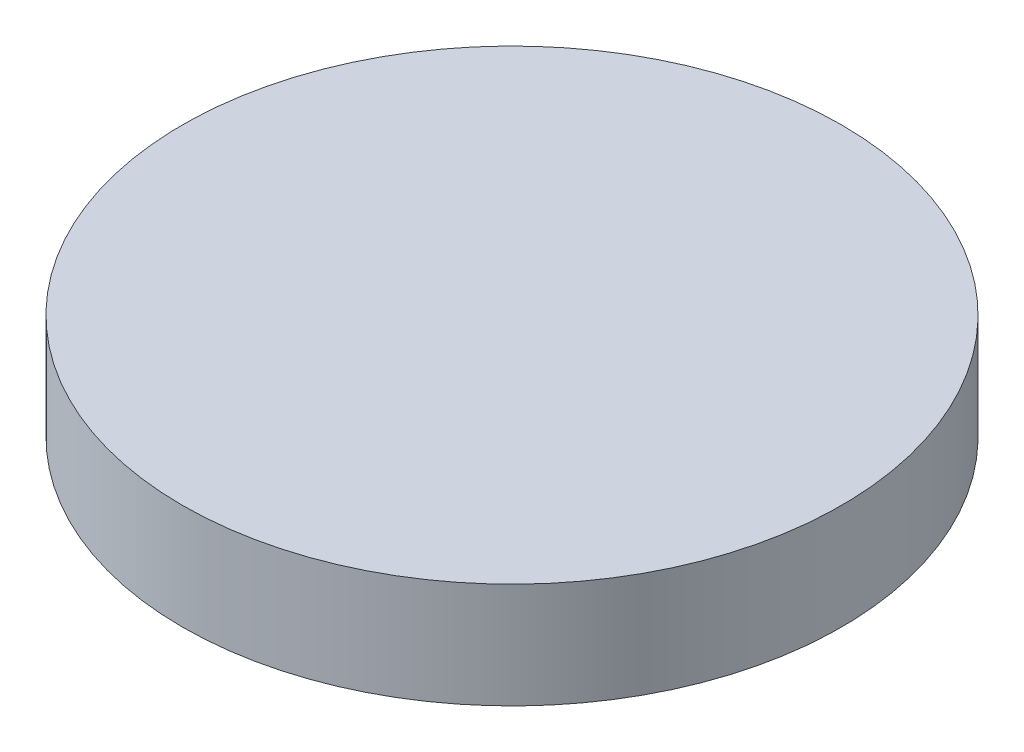
SolidWorks part; units mm, degrees
ref_plane "Front Plane" through (0, 0, 0) normal (0, 0, 1) x (1, 0, 0)
ref_plane "Top Plane" through (0, 0, 0) normal (0, 1, 0) x (1, 0, 0)
ref_plane "Right Plane" through (0, 0, 0) normal (1, 0, 0) x (0, 0, -1)
sketch "Sketch1" plane through (0, 0, 0) normal (0, 1, 0) x (1, 0, 0)
  circle A0 centre (0, 0) radius 25.4
  dimension "D1" = 50.8
extrude "Boss-Extrude1" add sketch "Sketch1" along normal blind 8.128 contours A0
